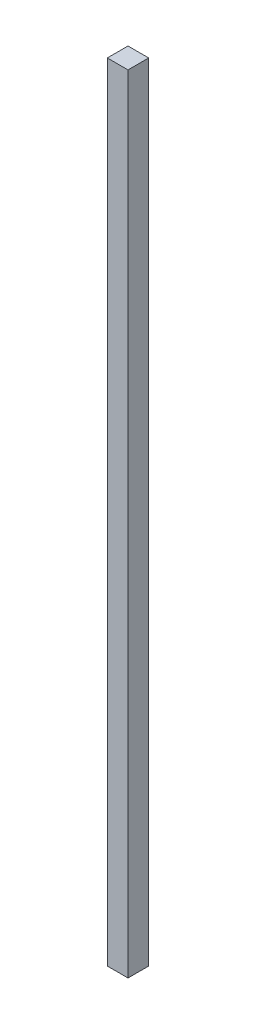
SolidWorks part; units mm, degrees
ref_plane "Спереди" through (0, 0, 0) normal (0, 0, 1) x (1, 0, 0)
ref_plane "Сверху" through (0, 0, 0) normal (0, 1, 0) x (1, 0, 0)
ref_plane "Справа" through (0, 0, 0) normal (1, 0, 0) x (0, 0, -1)
other "Configuration Table"
sketch "Эскиз1" plane through (0, 0, 0) normal (0, 1, 0) x (1, 0, 0)
  line L1 (25, 25) -> (-25, 25)
  line L2 (25, 25) -> (25, -25)
  line L3 (25, -25) -> (-25, -25)
  line L4 (-25, 25) -> (-25, -25)
  line L5 (25, 25) -> (-25, -25) construction
  line L6 (25, -25) -> (-25, 25) construction
  point P0 (0, 0)
extrude "Бобышка-Вытянуть1" add sketch "Эскиз1" along normal blind 1900
